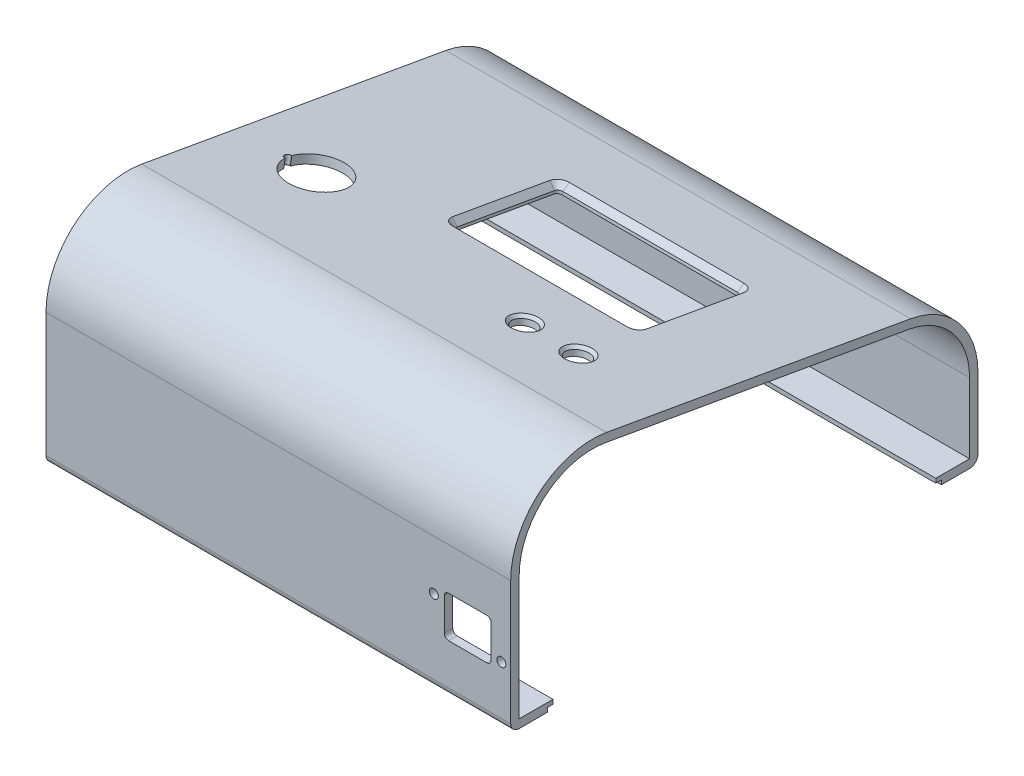
SolidWorks part; units mm, degrees
ref_plane "Front Plane" through (0, 0, 0) normal (0, 0, 1) x (1, 0, 0)
ref_plane "Top Plane" through (0, 0, 0) normal (0, 1, 0) x (1, 0, 0)
ref_plane "Right Plane" through (0, 0, 0) normal (1, 0, 0) x (0, 0, -1)
sketch "Sketch1" plane through (0, 0, 0) normal (1, 0, 0) x (0, 0, -1)
  line L0 (-80, -33.5217) -> (-80, 10.5217)
  line L1 (-49.4851, 36.1267) -> (58.5149, 17.0833)
  line L2 (80, -8.5217) -> (80, -33.5217)
  line L3 (80, -36.5217) -> (68, -36.5217)
  line L4 (-68, -36.5217) -> (-80, -36.5217)
  line L5 (-80, -36.5217) -> (80, -36.5217) construction
  line L6 (-54, 36.5217) -> (40.1832, 36.5217) construction
  line L7 (0, -36.5217) -> (0, 36.5217) construction
  line L8 (80, -33.5217) -> (68, -33.5217)
  line L9 (-83, -33.5217) -> (-83, 10.5217)
  line L10 (-48.9642, 39.0811) -> (59.0358, 20.0378)
  line L11 (83, -8.5217) -> (83, -33.5217)
  line L12 (68, -33.5217) -> (68, -36.5217)
  line L13 (-80, -33.5217) -> (-68, -33.5217)
  line L14 (-68, -33.5217) -> (-68, -36.5217)
  line L15 (83, -8.5217) -> (83, -39.5217) construction
  line L16 (83, -39.5217) -> (79.3197, -39.5217) construction
  line L17 (-83, -39.2753) -> (-54.8619, -41.6896) construction
  line L18 (-83, -39.2753) -> (-83, 10.5217) construction
  line L19 (80, -36.5217) -> (79.3197, -36.5217) construction
  line L20 (-80, -36.5217) -> (-54.6054, -38.7006) construction
  line L21 (-80, -36.5217) -> (-80, 10.5217) construction
  line L22 (80, -8.5217) -> (80, -36.5217) construction
  arc A0 (58.5149, 17.0833) -> (80, -8.5217) centre (54, -8.5217) cw
  arc A1 (-80, 10.5217) -> (-49.4851, 36.1267) centre (-54, 10.5217) cw
  arc A2 (-83, 10.5217) -> (-48.9642, 39.0811) centre (-54, 10.5217) cw
  arc A3 (59.0358, 20.0378) -> (83, -8.5217) centre (54, -8.5217) cw
  arc A4 (83, -33.5217) -> (80, -36.5217) centre (80, -33.5217) cw
  arc A5 (-83, -33.5217) -> (-80, -36.5217) centre (-80, -33.5217) ccw
  point P24 (0, 0)
  point P27 (0, -36.5217)
  dimension "D1" = 26
  dimension "D7" = 3
  dimension "D9" = 3
  dimension "D2" = 100
  dimension "D3" = 28
  dimension "D4" = 3
  dimension "D5" = 166
  dimension "D6" = 12
  dimension "D8" = 109.6661
extrude "Boss-Extrude1" add sketch "Sketch1" along normal mid plane 165.1
sketch "Sketch2" plane through (0, 29.5293, -5.2068) normal (0, 0.9848, -0.1736) x (1, 0, 0)
  line L0 (15, 29.6594) -> (15, -8.4406) construction
  line L1 (-16, -8.4406) -> (46, -8.4406)
  line L2 (-17.5, -6.9406) -> (-17.5, 28.1594)
  line L3 (-16, 29.6594) -> (46, 29.6594)
  line L4 (47.5, -6.9406) -> (47.5, 28.1594)
  line L5 (82.55, -55.0067) -> (82.55, 54.6594) construction
  line L6 (82.55, 54.6594) -> (-82.55, 54.6594) construction
  arc A0 (46, 29.6594) -> (47.5, 28.1594) centre (46, 28.1594) cw
  arc A1 (46, -8.4406) -> (47.5, -6.9406) centre (46, -6.9406) ccw
  arc A2 (-16, -8.4406) -> (-17.5, -6.9406) centre (-16, -6.9406) cw
  arc A3 (-17.5, 28.1594) -> (-16, 29.6594) centre (-16, 28.1594) cw
  dimension "D1" = 1.5
  dimension "D2" = 38.1
  dimension "D3" = 65
  dimension "D4" = 25
  dimension "D5" = 67.55
extrude "Cut-Extrude1" cut sketch "Sketch2" against normal up to next
sketch "Sketch3" plane through (0, 29.5293, -5.2068) normal (0, 0.9848, -0.1736) x (1, 0, 0)
  line L0 (-16, -8.4406) -> (46, -8.4406) construction
  line L1 (82.55, 54.6594) -> (82.55, -55.0067) construction
  line L2 (-54.85, -20.1506) -> (-61.0545, -20.1506) construction
  line L3 (-64.7777, -18.9506) -> (-65.05, -18.9506)
  line L4 (-17.5, -6.9406) -> (-17.5, 28.1594) construction
  line L5 (-16, -8.4406) -> (46, -8.4406) construction
  line L6 (-66.05, -19.9506) -> (-66.05, -20.3506)
  line L7 (-65.05, -21.3506) -> (-64.7777, -21.3506)
  circle A0 centre (49.2, -31.2543) radius 3.97
  circle A1 centre (30.15, -31.2543) radius 3.97
  arc A2 (-64.7777, -21.3506) -> (-64.7777, -18.9506) centre (-54.85, -20.1506) ccw
  arc A3 (-66.05, -20.3506) -> (-65.05, -21.3506) centre (-65.05, -20.3506) ccw
  arc A4 (-65.05, -18.9506) -> (-66.05, -19.9506) centre (-65.05, -19.9506) ccw
  point P10 (-44.85, -20.1506)
  dimension "D1" = 7.94
  dimension "D2" = 19.05
  dimension "D3" = 37.35
  dimension "D4" = 33.35
  dimension "D5" = 20
  dimension "D6" = 11.71
  dimension "D7" = 22.8137
  dimension "D8" = 1
  dimension "D9" = 2.4
  dimension "D10" = 21.2
extrude "Cut-Extrude2" cut sketch "Sketch3" against normal up to next
sketch "Sketch5" plane through (0, 26.5748, -4.6859) normal (0, -0.9848, 0.1736) x (1, 0, 0)
  line L0 (-16, -29.6594) -> (46, -29.6594) construction
  line L1 (-28.95, 7.9906) -> (57.15, 7.9906) construction
  line L2 (-28.95, 7.9906) -> (-28.95, -23.7594) construction
  line L3 (-28.95, -23.7594) -> (57.15, -23.7594) construction
  line L4 (57.15, 7.9906) -> (57.15, -23.7594) construction
  line L6 (14.1, -23.7594) -> (14.1, 0) construction
  line L7 (82.55, 55.0067) -> (82.55, -54.6594) construction
  line L8 (47.5, -28.1594) -> (47.5, 6.9406) construction
  line L9 (-17.5, 6.9406) -> (-17.5, -28.1594) construction
  circle A0 centre (57.15, -23.7594) radius 4.15
  circle A1 centre (-28.95, -23.7594) radius 4.15
  circle A2 centre (-28.95, 7.9906) radius 4.15
  circle A3 centre (57.15, 7.9906) radius 4.15
  dimension "D1" = 8.3
  dimension "D5" = 68.45
  dimension "D6" = 9.65
  dimension "D7" = 11.45
  dimension "D2" = 86.1
  dimension "D3" = 31.75
  dimension "D4" = 5.9
extrude "Cut-Extrude4" cut sketch "Sketch5" against normal blind 1
sketch "Sketch6" plane through (0, 0, 83) normal (0, 0, 1) x (1, 0, 0)
  line L0 (82.55, 10.5217) -> (82.55, -33.5217) construction
  line L1 (60.45, -4.4217) -> (74.05, -4.4217)
  line L2 (58.95, -5.9217) -> (58.95, -17.5217)
  line L3 (60.45, -19.0217) -> (74.05, -19.0217)
  line L4 (75.55, -5.9217) -> (75.55, -17.5217)
  line L5 (82.55, -36.5217) -> (-82.55, -36.5217) construction
  arc A0 (74.05, -19.0217) -> (75.55, -17.5217) centre (74.05, -17.5217) ccw
  arc A1 (74.05, -4.4217) -> (75.55, -5.9217) centre (74.05, -5.9217) cw
  arc A2 (60.45, -4.4217) -> (58.95, -5.9217) centre (60.45, -5.9217) ccw
  arc A3 (58.95, -17.5217) -> (60.45, -19.0217) centre (60.45, -17.5217) ccw
  circle A4 centre (79.225, -16.1967) radius 1.6
  circle A5 centre (55.225, -7.1967) radius 1.6
  dimension "D1" = 1.5
  dimension "D6" = 3.2
  dimension "D7" = 3.725
  dimension "D8" = 2.775
  dimension "D9" = 24
  dimension "D10" = 9
  dimension "D2" = 16.6
  dimension "D3" = 14.6
  dimension "D4" = 7
  dimension "D5" = 17.5
extrude "Cut-Extrude5" cut sketch "Sketch6" against normal up to next
chamfer "Chamfer1" distance 2 angle 45 8 edges at (15, 24.379, -34.4156) (-17.0607, 24.4553, -33.9829) (47.0607, 24.4553, -33.9829) (-17.5, 27.687, -15.655) (47.5, 27.687, -15.655) (-17.0607, 30.9187, 2.6729) (47.0607, 30.9187, 2.6729) (15, 30.995, 3.1056)
chamfer "Chamfer2" distance 1 angle 45 2 edges at (30.15, 35.6459, 29.4823) (49.2, 35.6459, 29.4823)
sketch "Sketch7" plane through (0, -36.5217, 0) normal (0, -1, 0) x (1, 0, 0)
  line L0 (82.55, 80) -> (82.55, 68) construction
  line L1 (-82.55, 68) -> (82.55, 68)
  line L2 (-82.55, 68) -> (-82.55, 70)
  line L3 (-82.55, 70) -> (82.55, 70)
  line L4 (82.55, 68) -> (82.55, 70)
  line L5 (-82.55, -68) -> (-82.55, -80) construction
  line L6 (82.55, -68) -> (-82.55, -68)
  line L7 (82.55, -68) -> (82.55, -70)
  line L8 (82.55, -70) -> (-82.55, -70)
  line L9 (-82.55, -68) -> (-82.55, -70)
  dimension "D1" = 2
  dimension "D2" = 2
extrude "Cut-Extrude6" cut sketch "Sketch7" against normal blind 1.5
